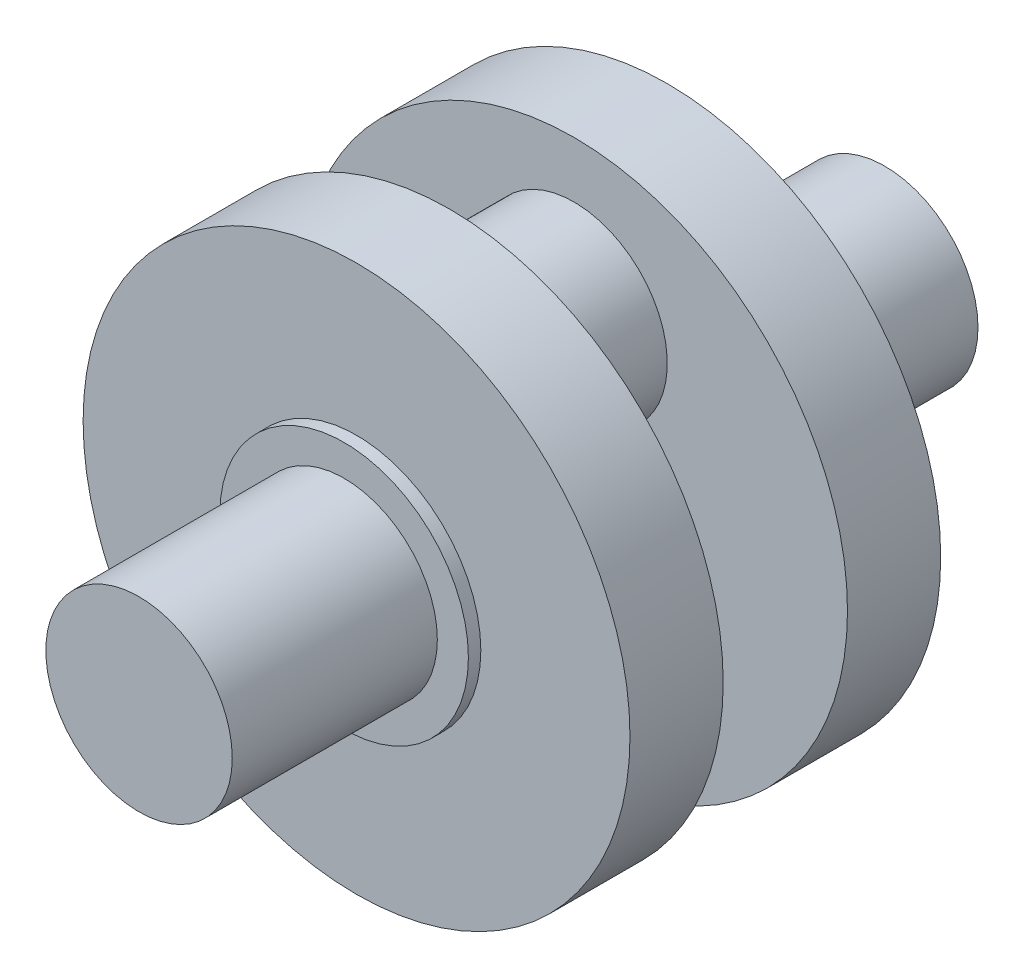
SolidWorks part; units mm, degrees
ref_plane "Płaszczyzna przednia" through (0, 0, 0) normal (0, 0, 1) x (1, 0, 0)
ref_plane "Płaszczyzna górna" through (0, 0, 0) normal (0, 1, 0) x (1, 0, 0)
ref_plane "Płaszczyzna prawa" through (0, 0, 0) normal (1, 0, 0) x (0, 0, -1)
sketch "Szkic1" plane through (0, 0, 0) normal (0, 0, 1) x (1, 0, 0)
  circle A0 centre (0, 0) radius 15
  dimension "D1" = 30
extrude "Dodanie-wyciągnięcie1" add sketch "Szkic1" along normal blind 33
sketch "Szkic3" plane through (0, 0, 0) normal (0, 0, -1) x (-1, 0, 0)
  circle A0 centre (0, 0) radius 20
  dimension "D1" = 40
extrude "Dodanie-wyciągnięcie3" add sketch "Szkic3" along normal blind 2
sketch "Szkic5" plane through (0, 0, -2) normal (0, 0, -1) x (-1, 0, 0)
  circle A0 centre (0, 0) radius 44
  dimension "D1" = 88
extrude "Dodanie-wyciągnięcie4" add sketch "Szkic5" along normal blind 15
sketch "Szkic6" plane through (0, 0, -17) normal (0, 0, -1) x (-1, 0, 0)
  circle A0 centre (0, 20) radius 15
  point P2 (0, 0)
  dimension "D2" = 30
  dimension "D1" = 20
extrude "Dodanie-wyciągnięcie5" add sketch "Szkic6" along normal blind 10
mirror "Lustro5" about plane through (0, 20, -27) normal (0, 0, -1) of bodies 105
